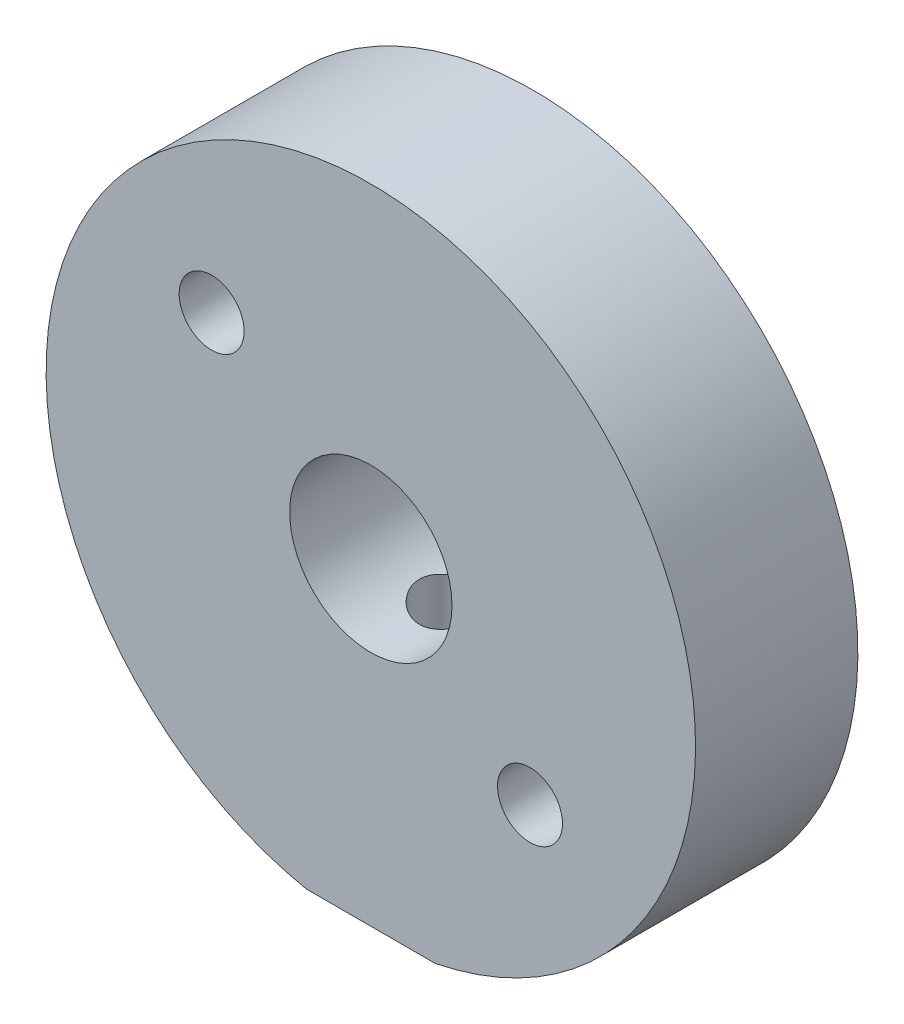
SolidWorks part; units mm, degrees
ref_plane "Front Plane" through (0, 0, 0) normal (0, 0, 1) x (1, 0, 0)
ref_plane "Top Plane" through (0, 0, 0) normal (0, 1, 0) x (1, 0, 0)
ref_plane "Right Plane" through (0, 0, 0) normal (1, 0, 0) x (0, 0, -1)
sketch "Sketch1" plane through (0, 0, 0) normal (0, 0, 1) x (1, 0, 0)
  circle A0 centre (0, 0) radius 5
  circle A1 centre (0, 0) radius 1.25
extrude "Extrude1" add sketch "Sketch1" along normal mid plane 2.5
sketch "Sketch2" plane through (0, 0, 0) normal (0, 0, 1) x (1, 0, 0)
  line L0 (-2.4513, 2.0569) -> (0, 0)
  circle A0 centre (0, 0) radius 3.2 construction
  circle A1 centre (-2.4513, 2.0569) radius 0.5
  circle A4 centre (2.4513, -2.0569) radius 0.5
  circle A6 centre (-2.0569, -2.4513) radius 0.5 [skipped]
  circle A7 centre (2.0569, 2.4513) radius 0.5 [skipped]
  dimension "D1" = 4
  dimension "D2" = 6.4
extrude "Extrude2" cut sketch "Sketch2" against normal through all both and the other way through all
sketch "Sketch3" plane through (0, 0, 0) normal (0, 1, 0) x (1, 0, 0)
  circle A0 centre (0, 0) radius 0.5
extrude "Extrude3" cut sketch "Sketch3" against normal through all
sketch "Sketch4" plane through (0, 0, 0) normal (0, 0, 1) x (1, 0, 0)
  line L0 (0, 0) -> (0, -4.9)
  line L2 (0, -4.9) -> (-4.2055, -4.9)
  line L3 (0, -4.9) -> (0, -5.4728)
  line L4 (0, -5.4728) -> (-4.2055, -5.4728)
  line L5 (-4.2055, -4.9) -> (-4.2055, -5.4728)
  line L6 (0, -4.9) -> (4.0922, -4.9)
  line L7 (0, -4.9) -> (0, -5.4728)
  line L8 (0, -5.4728) -> (4.0922, -5.4728)
  line L9 (4.0922, -4.9) -> (4.0922, -5.4728)
extrude "Extrude4" cut sketch "Sketch4" against normal through all both and the other way through all contours L2 L5 L4 L3 | L9 L6 L3 L8
